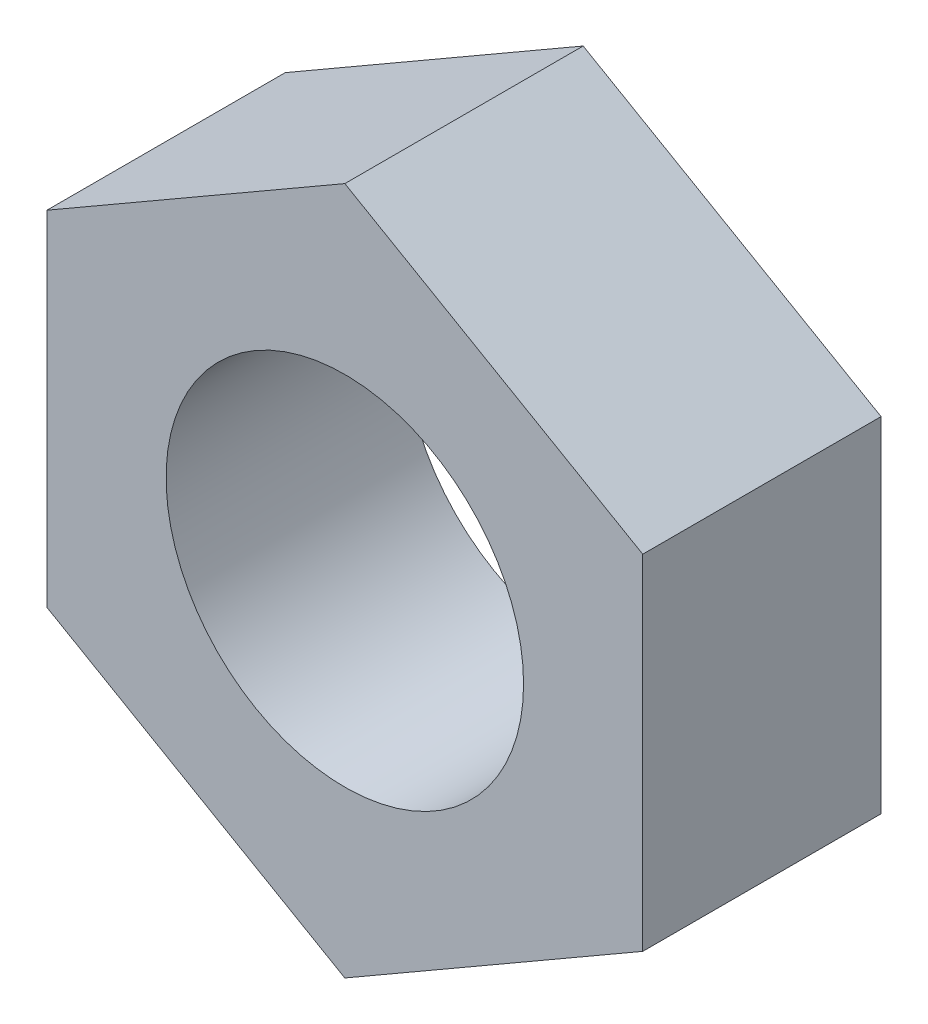
SolidWorks part; units mm, degrees
ref_plane "前视基准面" through (0, 0, 0) normal (0, 0, 1) x (1, 0, 0)
ref_plane "上视基准面" through (0, 0, 0) normal (0, 1, 0) x (1, 0, 0)
ref_plane "右视基准面" through (0, 0, 0) normal (1, 0, 0) x (0, 0, -1)
sketch "草图1" plane through (0, 0, 0) normal (0, 0, 1) x (1, 0, 0)
  line L5 (0, 2.8868) -> (-2.5, 1.4434)
  line L6 (-2.5, 1.4434) -> (-2.5, -1.4434)
  line L7 (-2.5, -1.4434) -> (0, -2.8868)
  line L8 (0, -2.8868) -> (2.5, -1.4434)
  line L9 (2.5, -1.4434) -> (2.5, 1.4434)
  line L10 (2.5, 1.4434) -> (0, 2.8868)
  circle A0 centre (0, 0) radius 2.5 construction
  circle A1 centre (0, 0) radius 1.5
  dimension "D2" = 3
  dimension "D1" = 5
extrude "凸台-拉伸1" add sketch "草图1" along normal blind 2
